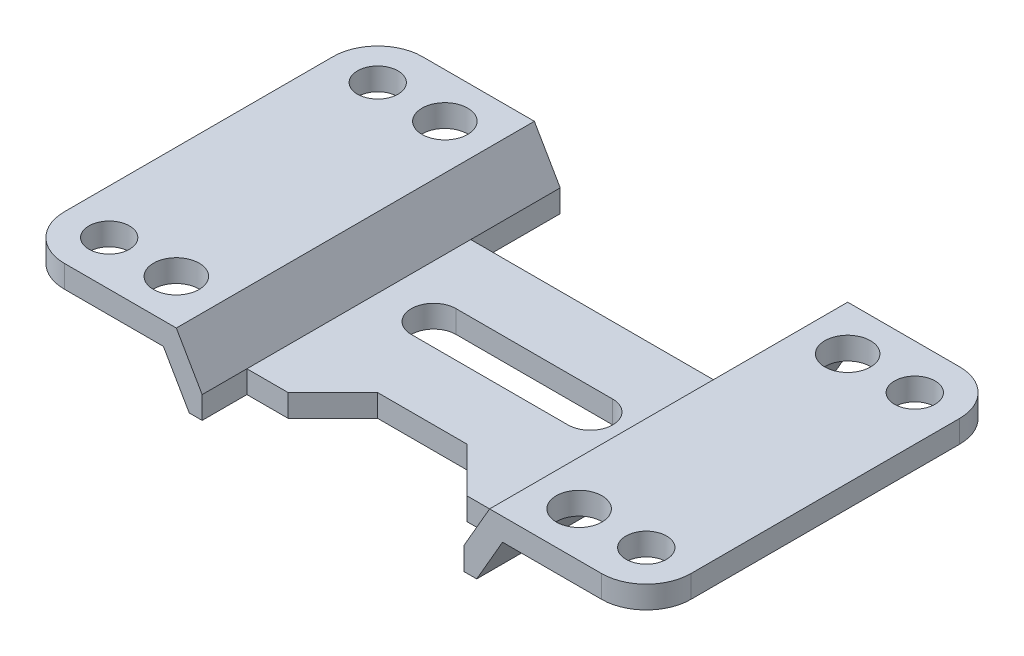
SolidWorks part; units mm, degrees
material "Plain Carbon Steel"
ref_plane "Front Plane" through (0, 0, 0) normal (0, 0, 1) x (1, 0, 0)
ref_plane "Top Plane" through (0, 0, 0) normal (0, 1, 0) x (1, 0, 0)
ref_plane "Right Plane" through (0, 0, 0) normal (1, 0, 0) x (0, 0, -1)
sketch "Sketch1" plane through (0, 0, 0) normal (0, 0, 1) x (1, 0, 0)
  line L0 (0, 0) -> (-37.1177, 0)
  line L1 (-37.1177, 0) -> (-44.45, 12.7)
  line L2 (-44.45, 12.7) -> (-88.9, 12.7)
  line L3 (-88.9, 12.7) -> (-88.9, 6.35)
  line L4 (-88.9, 6.35) -> (-48.1162, 6.35)
  line L5 (-48.1162, 6.35) -> (-40.7838, -6.35)
  line L6 (-40.7838, -6.35) -> (40.7838, -6.35)
  line L7 (40.7838, -6.35) -> (48.1162, 6.35)
  line L8 (48.1162, 6.35) -> (88.9, 6.35)
  line L9 (88.9, 6.35) -> (88.9, 12.7)
  line L10 (88.9, 12.7) -> (44.45, 12.7)
  line L11 (44.45, 12.7) -> (37.1177, 0)
  line L12 (37.1177, 0) -> (0, 0)
  point P6 (-66.675, 12.7)
  point P15 (-18.5588, 0)
  dimension "D1" = 6.35
  dimension "D2" = 6.35
  dimension "D3" = 6.35
  dimension "D5" = 120
  dimension "D6" = 120
  dimension "D7" = 44.45
  dimension "D8" = 44.45
  dimension "D4" = 6.35
  dimension "D9" = 19.05
  dimension "D10" = 88.9
  dimension "D11" = 44.45
extrude "Boss-Extrude1" add sketch "Sketch1" along normal mid plane 101.6
sketch "Sketch2" plane through (0, 0, 0) normal (0, 1, 0) x (1, 0, 0)
  line L0 (-37.1177, 25.4) -> (37.1177, 25.4)
  line L1 (-37.1177, -50.8) -> (-37.1177, 50.8) construction
  line L2 (37.1177, -50.8) -> (37.1177, 50.8) construction
  line L3 (37.1177, 25.4) -> (37.1177, 50.8)
  line L4 (37.1177, 50.8) -> (-37.1177, 50.8)
  line L5 (-37.1177, 50.8) -> (-37.1177, 25.4)
  line L6 (-37.1177, -38.1) -> (-25.4, -38.1)
  line L7 (-25.4, -38.1) -> (-12.7, -25.4)
  line L8 (-12.7, -25.4) -> (12.7, -25.4)
  line L9 (12.7, -25.4) -> (25.4, -38.1)
  line L10 (25.4, -38.1) -> (37.1177, -38.1)
  line L11 (37.1177, -38.1) -> (37.1177, -50.8)
  line L12 (37.1177, -50.8) -> (-37.1177, -50.8) construction
  line L13 (37.1177, -50.8) -> (-37.1177, -50.8)
  line L14 (-37.1177, -50.8) -> (-37.1177, -38.1)
  line L15 (-22.225, 0) -> (22.225, 0) construction
  line L16 (-22.225, 6.35) -> (22.225, 6.35)
  line L17 (-22.225, -6.35) -> (22.225, -6.35)
  arc A0 (-22.225, 6.35) -> (-22.225, -6.35) centre (-22.225, 0) ccw
  arc A1 (22.225, -6.35) -> (22.225, 6.35) centre (22.225, 0) ccw
  point P24 (0, 0)
  dimension "D9" = 6.35
  dimension "D1" = 25.4
  dimension "D2" = 12.7
  dimension "D3" = 12.7
  dimension "D4" = 25.4
  dimension "D5" = 45
  dimension "D6" = 45
  dimension "D7" = 12.7
  dimension "D8" = 44.45
extrude "Cut-Extrude1" cut sketch "Sketch2" against normal through all
fillet "Fillet2" radius 12.7 4 edges at (-88.9, 9.525, -50.8) (88.9, 9.525, 50.8) (88.9, 9.525, -50.8) (-88.9, 9.525, 50.8)
sketch "Sketch4" plane through (0, 12.7, 0) normal (0, 1, 0) x (1, 0, 0)
  line L0 (-88.9, -38.1) -> (-88.9, 38.1) construction
  line L1 (0, 0) -> (0, 25.4) construction
  line L2 (-37.1177, 25.4) -> (37.1177, 25.4) construction
  circle A1 centre (-57.15, 38.1) radius 6.477
  circle A3 centre (-57.15, -38.1) radius 6.477
  circle A4 centre (57.15, -38.1) radius 6.477
  circle A5 centre (57.15, 38.1) radius 6.477
  dimension "D1" = 31.75
  dimension "D4" = 12.954
  dimension "D2" = 38.1
  dimension "D3" = 76.2
extrude "Cut-Extrude2" cut sketch "Sketch4" against normal through all
sketch "Sketch5" plane through (0, 12.7, 0) normal (0, 1, 0) x (1, 0, 0)
  point P0 (-76.2, 38.1)
  point P1 (-76.2, -38.1)
  point P3 (76.2, -38.1)
  point P5 (76.2, 38.1)
hole_wizard "1/2-20 Tapped Hole1" positions "Sketch5" profile "Sketch6" tap size "1/2-20" standard "ANSI Inch" end condition up to next
sketch "Sketch6" plane through (-76.2, 12.7, -38.1) normal (1, 0, 0) x (0, 0, 1)
  line L0 (0, 0) -> (0, 6.35)
  line L1 (0, 6.35) -> (5.7544, 6.35)
  line L2 (5.7544, 6.35) -> (5.7544, 0)
  line L5 (5.7544, 0) -> (0, 0)
  line L11 (0, -6.35) -> (0, 107.95) construction
  dimension "Thru Tap Drill Dia." = 11.5087
  dimension "Thru Tap Drill Depth" = 6.35
cosmetic thread "Hole Thread1" parameters "D2"=12.7
cosmetic thread "Hole Thread2" parameters "D2"=12.7
cosmetic thread "Hole Thread3" parameters "D2"=12.7
cosmetic thread "Hole Thread4" parameters "D2"=12.7
equation "\"D2@Sketch1\"=\"D1@Sketch1\""
equation "\"D3@Sketch1\"=\"D1@Sketch1\""
equation "\"D8@Sketch1\"=\"D7@Sketch1\""
equation "\"D4@Sketch1\"=\"D1@Sketch1\""
